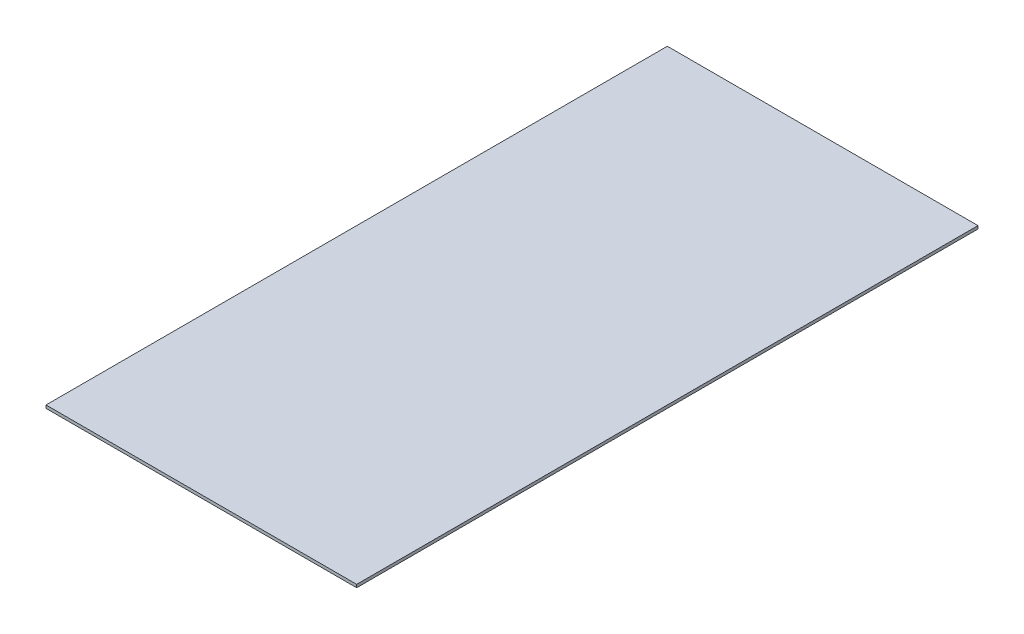
SolidWorks part; units mm, degrees
ref_plane "Front Plane" through (0, 0, 0) normal (0, 0, 1) x (1, 0, 0)
ref_plane "Top Plane" through (0, 0, 0) normal (0, 1, 0) x (1, 0, 0)
ref_plane "Right Plane" through (0, 0, 0) normal (1, 0, 0) x (0, 0, -1)
sketch "Sketch1" plane through (0, 0, 0) normal (0, 1, 0) x (1, 0, 0)
  line L1 (-152.4, -304.8) -> (152.4, -304.8)
  line L2 (-152.4, -304.8) -> (-152.4, 304.8)
  line L3 (-152.4, 304.8) -> (152.4, 304.8)
  line L4 (152.4, -304.8) -> (152.4, 304.8)
  line L5 (-152.4, -304.8) -> (152.4, 304.8) construction
  line L6 (-152.4, 304.8) -> (152.4, -304.8) construction
  point P0 (0, 0)
  dimension "D1" = 304.8
  dimension "D2" = 609.6
extrude "Boss-Extrude1" add sketch "Sketch1" along normal mid plane 2.921
